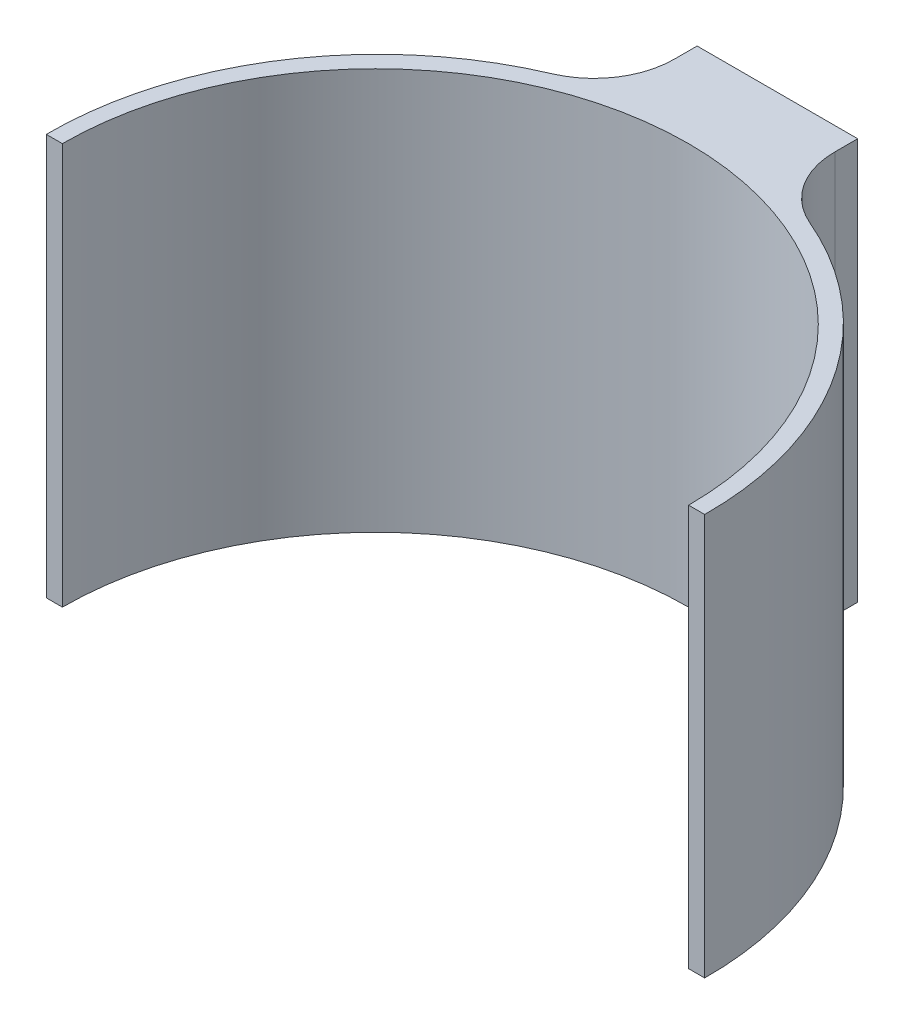
SolidWorks part; units mm, degrees
ref_plane "Plan de face" through (0, 0, 0) normal (0, 0, 1) x (1, 0, 0)
ref_plane "Plan de dessus" through (0, 0, 0) normal (0, 1, 0) x (1, 0, 0)
ref_plane "Plan de droite" through (0, 0, 0) normal (1, 0, 0) x (0, 0, -1)
sketch "Esquisse1" plane through (0, 0, 0) normal (0, 1, 0) x (1, 0, 0)
  line L0 (0, 0) -> (-2, 0)
  line L1 (78, 0) -> (80, 0)
  line L2 (49, 40.0581) -> (49, 50.0581)
  line L3 (49, 50.0581) -> (29, 50.0581)
  line L4 (29, 50.0581) -> (29, 40.0581)
  arc A0 (0, 0) -> (78, 0) centre (39, 0) cw
  arc A1 (-2, 0) -> (29, 40.0581) centre (39, 0.2952) cw
  arc A2 (49, 40.0581) -> (80, 0) centre (39, 0.2952) cw
  point P9 (39, 50.0581)
  point P12 (39, 39)
  dimension "D1" = 39
  dimension "D4" = 10
  dimension "D2" = 2
  dimension "D3" = 2
  dimension "D5" = 20
extrude "Boss.-Extru.1" add sketch "Esquisse1" along normal blind 50
fillet "Congé1" radius 10 2 edges at (49, 25, -40.0581) (29, 25, -40.0581)
